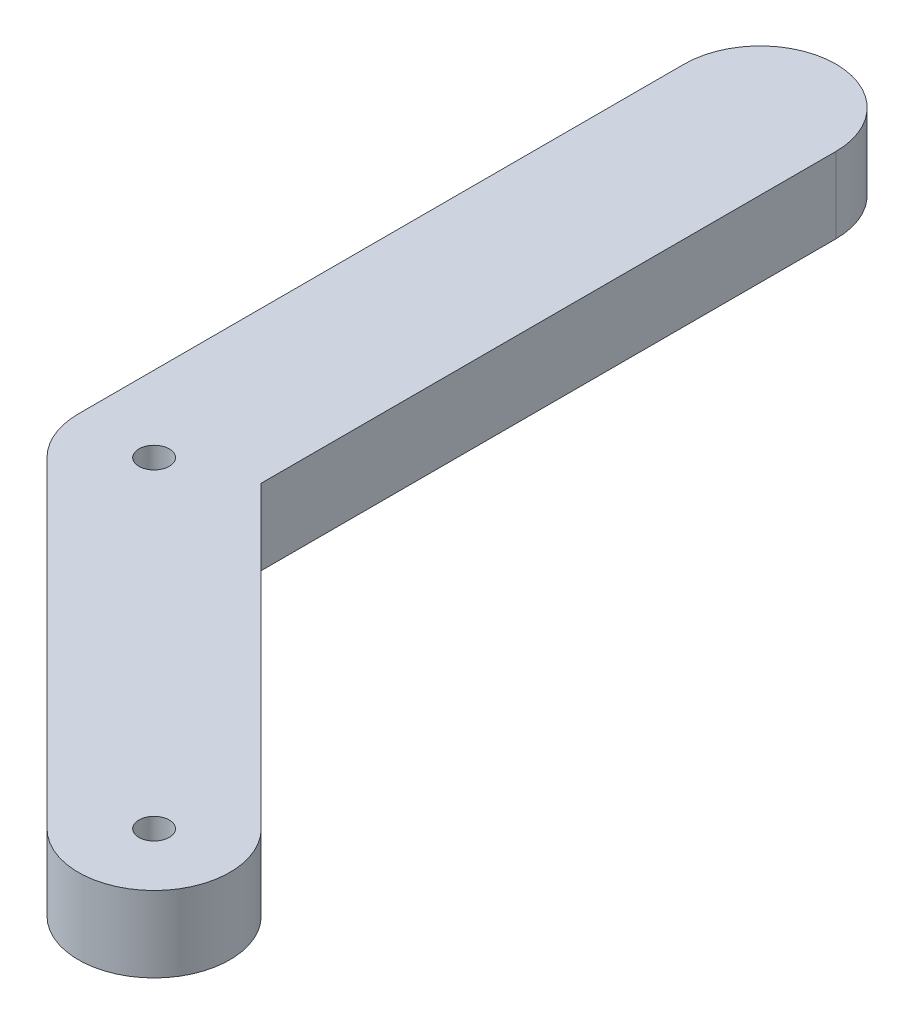
SolidWorks part; units mm, degrees
ref_plane "Front Plane" through (0, 0, 0) normal (0, 0, 1) x (1, 0, 0)
ref_plane "Top Plane" through (0, 0, 0) normal (0, 1, 0) x (1, 0, 0)
ref_plane "Right Plane" through (0, 0, 0) normal (1, 0, 0) x (0, 0, -1)
sketch "Sketch2" plane through (0, 0, 0) normal (0, 1, 0) x (1, 0, 0)
  line L0 (0, 0) -> (0, 40)
  line L1 (0, 0) -> (21.2132, -21.2132)
  dimension "D1" = 40
  dimension "D2" = 30
  dimension "D3" = 135
sketch "Sketch3" plane through (0, 0, 0) normal (0, 1, 0) x (1, 0, 0)
  line L0 (-5, 40) -> (-5, 0)
  line L1 (5, 40) -> (5, 2.0711)
  line L2 (-3.5355, -3.5355) -> (17.6777, -24.7487)
  line L3 (5, 2.0711) -> (24.7487, -17.6777)
  arc A1 (5, 40) -> (-5, 40) centre (0, 40) ccw
  arc A2 (-5, 0) -> (-3.5355, -3.5355) centre (0, 0) ccw
  circle A3 centre (0, 0) radius 1
  circle A4 centre (21.2132, -21.2132) radius 1
  arc A5 (17.6777, -24.7487) -> (24.7487, -17.6777) centre (21.2132, -21.2132) ccw
  dimension "D1" = 10
  dimension "D2" = 10
  dimension "D3" = 2
  dimension "D4" = 10
  dimension "D5" = 2
extrude "Boss-Extrude2" add sketch "Sketch3" along normal blind 5
